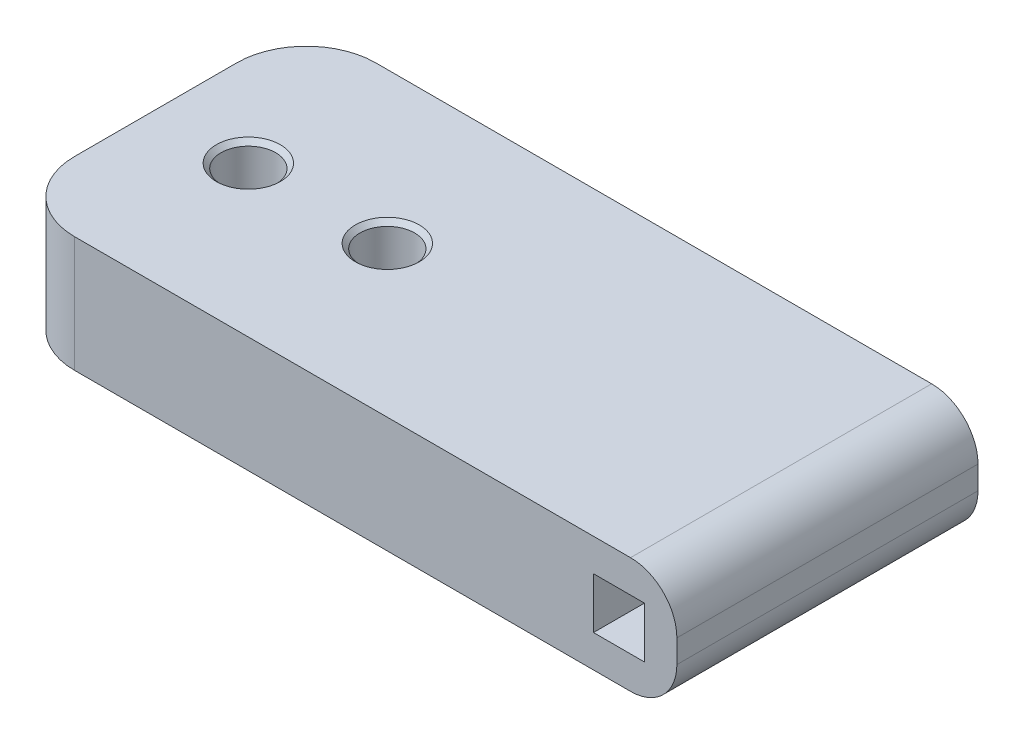
SolidWorks part; units mm, degrees
ref_plane "Front Plane" through (0, 0, 0) normal (0, 0, 1) x (1, 0, 0)
ref_plane "Top Plane" through (0, 0, 0) normal (0, 1, 0) x (1, 0, 0)
ref_plane "Right Plane" through (0, 0, 0) normal (1, 0, 0) x (0, 0, -1)
sketch "Sketch1" plane through (0, 0, 0) normal (0, 1, 0) x (1, 0, 0)
  line L1 (0, 0) -> (36.83, 0)
  line L2 (0, 0) -> (0, 16.51)
  line L3 (0, 16.51) -> (36.83, 16.51)
  line L4 (36.83, 0) -> (36.83, 16.51)
  dimension "D1" = 36.83
  dimension "D2" = 16.51
extrude "Boss-Extrude1" add sketch "Sketch1" along normal blind 6.35
hole_wizard "Ø3.0mm Dowel Hole1" positions "Sketch5" profile "Sketch4" hole size "Ø3.0" standard "ISO" end condition through all
sketch "Sketch5" plane through (0, 6.35, 0) normal (0, 1, 0) x (1, 0, 0)
  line L0 (0, 0) -> (36.83, 0) construction
  line L1 (0, 16.51) -> (0, 0) construction
  point P0 (5.08, 8.255)
  point P2 (12.7, 8.255)
  dimension "D1" = 8.255
  dimension "D2" = 5.08
  dimension "D3" = 7.62
sketch "Sketch4" plane through (5.08, 6.35, -8.255) normal (1, 0, 0) x (0, 0, 1)
  line L0 (0, 0) -> (0, 6.35)
  line L1 (0, 6.35) -> (1.5, 6.35)
  line L2 (1.5, 6.35) -> (1.5, 0)
  line L5 (1.5, 0) -> (0, 0)
  line L11 (0, -6.35) -> (0, 107.95) construction
  dimension "Thru Hole Dia." = 3
  dimension "Thru Hole Depth" = 6.35
chamfer "Chamfer1" distance 0.254 angle 45 4 edges at (12.7, 6.35, -6.755) (5.08, 6.35, -6.755) (5.08, 0, -6.755) (12.7, 0, -6.755)
fillet "Fillet2" radius 3.81 2 edges at (0, 3.175, 0) (0, 3.175, -16.51)
sketch "Sketch24" plane through (0, 0, 0) normal (0, 0, 1) x (1, 0, 0)
  line L0 (3.81, 6.35) -> (36.83, 6.35) construction
  line L1 (32.258, 4.572) -> (35.052, 4.572)
  line L2 (32.258, 4.572) -> (32.258, 1.778)
  line L3 (32.258, 1.778) -> (35.052, 1.778)
  line L4 (35.052, 4.572) -> (35.052, 1.778)
  line L5 (36.83, 6.35) -> (36.83, 0) construction
  dimension "D1" = 2.794
  dimension "D2" = 2.794
  dimension "D3" = 1.778
  dimension "D4" = 1.778
extrude "Cut-Extrude7" cut sketch "Sketch24" against normal blind 5.08
sketch "Sketch25" plane through (0, 0, -16.51) normal (0, 0, -1) x (-1, 0, 0)
  line L0 (-36.83, 6.35) -> (-36.83, 0) construction
  line L1 (-35.052, 1.778) -> (-32.258, 1.778)
  line L2 (-35.052, 1.778) -> (-35.052, 4.572)
  line L3 (-35.052, 4.572) -> (-32.258, 4.572)
  line L4 (-32.258, 1.778) -> (-32.258, 4.572)
  line L5 (-36.83, 6.35) -> (-3.81, 6.35) construction
  dimension "D1" = 1.778
  dimension "D2" = 2.794
  dimension "D3" = 1.778
  dimension "D4" = 2.794
extrude "Cut-Extrude8" cut sketch "Sketch25" against normal blind 5.08
fillet "Fillet7" radius 2.54 2 edges at (36.83, 0, -8.255) (36.83, 6.35, -8.255)
